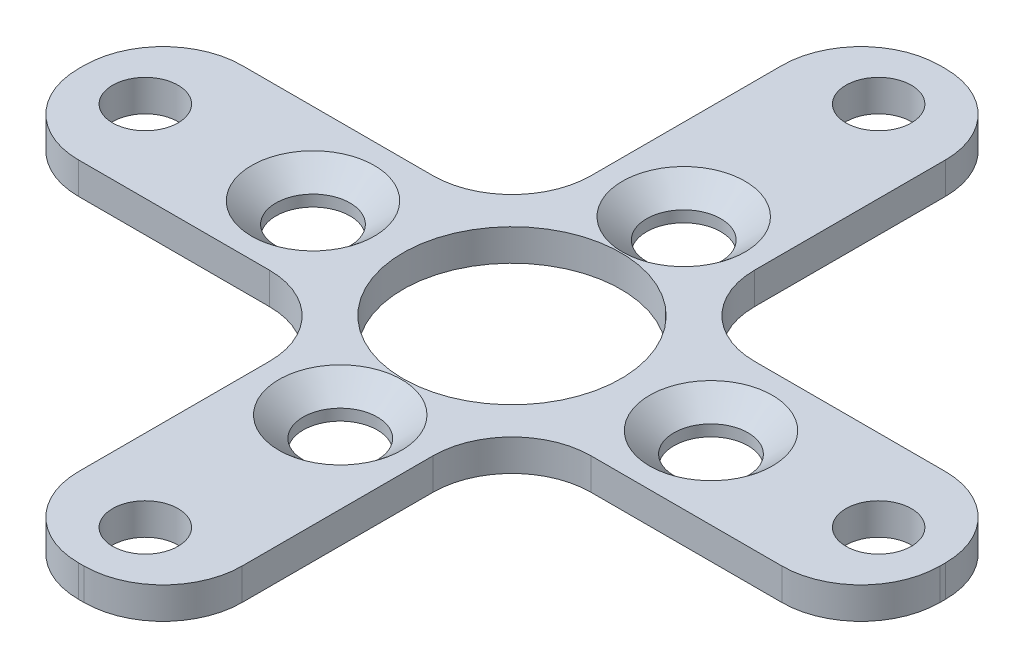
SolidWorks part; units mm, degrees
material "1060 Alloy"
ref_plane "Front" through (0, 0, 0) normal (0, 0, 1) x (1, 0, 0)
ref_plane "Top" through (0, 0, 0) normal (0, 1, 0) x (1, 0, 0)
ref_plane "Right" through (0, 0, 0) normal (1, 0, 0) x (0, 0, -1)
sketch "Sketch1" plane through (0, 0, 0) normal (0, 1, 0) x (1, 0, 0)
  line L0 (-3.81, 7.493) -> (-3.81, 16.383)
  line L1 (-0.127, -20.066) -> (0.127, -20.066)
  line L2 (-3.81, -16.383) -> (-3.81, -7.493)
  line L3 (-0.127, 20.066) -> (0.127, 20.066)
  line L4 (3.81, -16.383) -> (3.81, -7.493)
  line L5 (0, 17.0815) -> (0, -17.0815) construction
  line L6 (17.0815, 0) -> (-17.0815, 0) construction
  line L7 (-16.383, -3.81) -> (-7.493, -3.81)
  line L8 (-20.066, -0.127) -> (-20.066, 0.127)
  line L9 (-16.383, 3.81) -> (-7.493, 3.81)
  line L10 (20.066, -0.127) -> (20.066, 0.127)
  line L14 (7.493, 3.81) -> (16.383, 3.81)
  line L15 (3.81, 7.493) -> (3.81, 16.383)
  line L18 (7.493, -3.81) -> (16.383, -3.81)
  circle A0 centre (0, 0) radius 5.08
  arc A1 (-20.066, 0.127) -> (-16.383, 3.81) centre (-16.383, 0.127) cw
  arc A2 (-16.383, -3.81) -> (-20.066, -0.127) centre (-16.383, -0.127) cw
  arc A3 (-7.493, -3.81) -> (-3.81, -7.493) centre (-7.493, -7.493) cw
  arc A4 (3.81, -7.493) -> (7.493, -3.81) centre (7.493, -7.493) cw
  arc A5 (16.383, -3.81) -> (20.066, -0.127) centre (16.383, -0.127) ccw
  arc A6 (16.383, 3.81) -> (20.066, 0.127) centre (16.383, 0.127) cw
  arc A7 (7.493, 3.81) -> (3.81, 7.493) centre (7.493, 7.493) cw
  arc A8 (0.127, 20.066) -> (3.81, 16.383) centre (0.127, 16.383) cw
  arc A9 (-3.81, 16.383) -> (-0.127, 20.066) centre (-0.127, 16.383) cw
  arc A10 (-3.81, 7.493) -> (-7.493, 3.81) centre (-7.493, 7.493) cw
  arc A11 (0.127, -20.066) -> (3.81, -16.383) centre (0.127, -16.383) ccw
  arc A12 (-0.127, -20.066) -> (-3.81, -16.383) centre (-0.127, -16.383) cw
  circle A13 centre (0, 17.0815) radius 1.524
  circle A14 centre (17.0815, 0) radius 1.524
  circle A15 centre (-17.0815, 0) radius 1.524
  circle A16 centre (0, -17.0815) radius 1.524
  point P23 (3.81, -3.81)
  point P30 (3.81, 3.81)
  point P42 (0, 20.066)
  point P43 (20.066, 0)
  point P51 (0, 0)
  dimension "D1" = 3.683
  dimension "D2" = 3.683
  dimension "D5" = 10.16
  dimension "D9" = 3.048
  dimension "D3" = 7.62
  dimension "D4" = 7.62
  dimension "D6" = 40.132
  dimension "D7" = 40.132
  dimension "D8" = 34.163
extrude "Boss-Extrude1" add sketch "Sketch1" along normal blind 1.4732
hole_wizard "CSK for #4 Flat Head Machine Screw (100)2" positions "Sketch2" profile "Sketch3" countersink size "#4" standard "ANSI Inch"
sketch "Sketch2" plane through (0, 1.4732, 0) normal (0, 1, 0) x (1, 0, 0)
  line L0 (-9.271, 0) -> (9.271, 0) construction
  line L2 (0, 8.001) -> (0, -8.001) construction
  point P0 (0, 8.001)
  point P2 (0, -8.001)
  point P4 (9.271, 0)
  point P6 (-9.271, 0)
  dimension "D1" = 18.542
  dimension "D2" = 16.002
sketch "Sketch3" plane through (0, 1.4732, -8.001) normal (1, 0, 0) x (0, 0, 1)
  line L0 (0, 0) -> (0, 4.4871)
  line L1 (0, 4.4871) -> (1.7272, 3.4493)
  line L2 (1.7272, 3.4493) -> (1.7272, 0.9484)
  line L3 (1.7272, 0.9484) -> (2.8575, 0)
  line L5 (2.8575, 0) -> (0, 0)
  line L6 (-1.7272, 0.9484) -> (-2.8575, 0) construction
  line L10 (0, 4.4871) -> (-1.7272, 3.4493) construction
  line L11 (0, -6.35) -> (0, 107.95) construction
  dimension "Hole Dia." = 3.4544
  dimension "Hole Depth" = 3.4493
  dimension "Near C'Sink Dia." = 5.715
  dimension "Near C'Sink Angle" = 100
  dimension "Drill Angle" = 118
